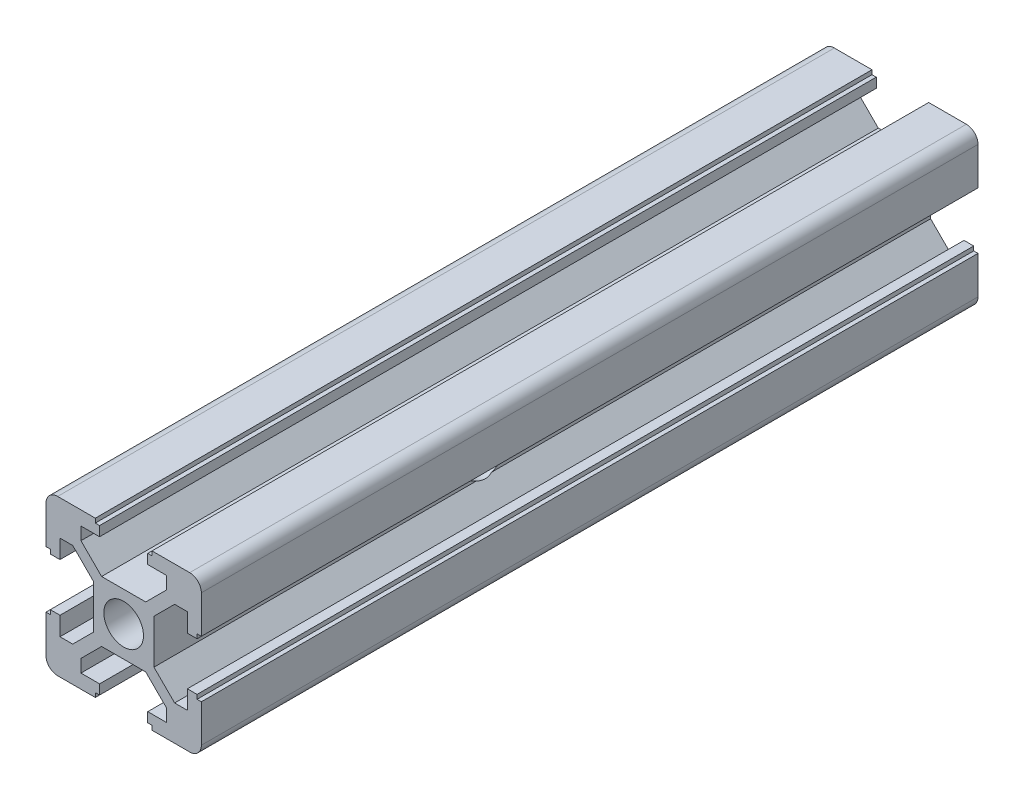
SolidWorks part; units mm, degrees
material "6063-T5"
ref_plane "前视基准面" through (0, 0, 0) normal (0, 0, 1) x (1, 0, 0)
ref_plane "上视基准面" through (0, 0, 0) normal (0, 1, 0) x (1, 0, 0)
ref_plane "右视基准面" through (0, 0, 0) normal (1, 0, 0) x (0, 0, -1)
sketch "草图2" plane through (0, 0, 0) normal (0, 0, 1) x (1, 0, 0)
  line L0 (-3.9, 2.8393) -> (-6.5607, 5.5)
  line L1 (-2.8393, 3.9) -> (2.8393, 3.9)
  line L2 (-3.9, 2.8393) -> (-3.9, -2.8393)
  line L3 (-2.8393, -3.9) -> (2.8393, -3.9)
  line L4 (3.9, 2.8393) -> (3.9, -2.8393)
  line L5 (-3.9, 3.9) -> (3.9, -3.9) construction
  line L6 (-3.9, -3.9) -> (3.9, 3.9) construction
  line L7 (-2.8393, 3.9) -> (-5.5, 6.5607)
  line L8 (-5.5, 6.5607) -> (-5.5, 8.2)
  line L9 (-5.5, 8.2) -> (-3.1, 8.2)
  line L10 (-3.1, 8.2) -> (-3.1, 9.45)
  line L11 (-3.1, 9.45) -> (-3.65, 9.45)
  line L12 (-3.65, 9.45) -> (-3.65, 10)
  line L13 (-3.65, 10) -> (-8.5, 10)
  line L14 (-6.5607, 5.5) -> (-8.2, 5.5)
  line L15 (-10, 3.65) -> (-10, 8.5)
  line L16 (-9.45, 3.65) -> (-10, 3.65)
  line L17 (-9.45, 3.1) -> (-9.45, 3.65)
  line L18 (-8.2, 3.1) -> (-9.45, 3.1)
  line L19 (-8.2, 5.5) -> (-8.2, 3.1)
  line L20 (2.8393, 3.9) -> (5.5, 6.5607)
  line L21 (3.9, 2.8393) -> (6.5607, 5.5)
  line L22 (6.5607, 5.5) -> (8.2, 5.5)
  line L23 (8.2, 5.5) -> (8.2, 3.1)
  line L24 (8.2, 3.1) -> (9.45, 3.1)
  line L25 (9.45, 3.1) -> (9.45, 3.65)
  line L26 (9.45, 3.65) -> (10, 3.65)
  line L27 (10, 3.65) -> (10, 8.5)
  line L28 (5.5, 6.5607) -> (5.5, 8.2)
  line L29 (3.65, 10) -> (8.5, 10)
  line L30 (3.65, 9.45) -> (3.65, 10)
  line L31 (3.1, 9.45) -> (3.65, 9.45)
  line L32 (3.1, 8.2) -> (3.1, 9.45)
  line L33 (5.5, 8.2) -> (3.1, 8.2)
  line L34 (3.9, -2.8393) -> (6.5607, -5.5)
  line L35 (2.8393, -3.9) -> (5.5, -6.5607)
  line L36 (5.5, -6.5607) -> (5.5, -8.2)
  line L37 (5.5, -8.2) -> (3.1, -8.2)
  line L38 (3.1, -8.2) -> (3.1, -9.45)
  line L39 (3.1, -9.45) -> (3.65, -9.45)
  line L40 (3.65, -9.45) -> (3.65, -10)
  line L41 (3.65, -10) -> (8.5, -10)
  line L42 (6.5607, -5.5) -> (8.2, -5.5)
  line L43 (10, -3.65) -> (10, -8.5)
  line L44 (9.45, -3.65) -> (10, -3.65)
  line L45 (9.45, -3.1) -> (9.45, -3.65)
  line L46 (8.2, -3.1) -> (9.45, -3.1)
  line L47 (8.2, -5.5) -> (8.2, -3.1)
  line L48 (-2.8393, -3.9) -> (-5.5, -6.5607)
  line L49 (-3.9, -2.8393) -> (-6.5607, -5.5)
  line L50 (-6.5607, -5.5) -> (-8.2, -5.5)
  line L51 (-8.2, -5.5) -> (-8.2, -3.1)
  line L52 (-8.2, -3.1) -> (-9.45, -3.1)
  line L53 (-9.45, -3.1) -> (-9.45, -3.65)
  line L54 (-9.45, -3.65) -> (-10, -3.65)
  line L55 (-10, -3.65) -> (-10, -8.5)
  line L56 (-5.5, -6.5607) -> (-5.5, -8.2)
  line L57 (-3.65, -10) -> (-8.5, -10)
  line L58 (-3.65, -9.45) -> (-3.65, -10)
  line L59 (-3.1, -9.45) -> (-3.65, -9.45)
  line L60 (-3.1, -8.2) -> (-3.1, -9.45)
  line L61 (-5.5, -8.2) -> (-3.1, -8.2)
  circle A0 centre (0, 0) radius 2.55
  arc A1 (-8.5, 10) -> (-10, 8.5) centre (-8.5, 8.5) ccw
  arc A2 (10, 8.5) -> (8.5, 10) centre (8.5, 8.5) ccw
  arc A3 (8.5, -10) -> (10, -8.5) centre (8.5, -8.5) ccw
  arc A4 (-10, -8.5) -> (-8.5, -10) centre (-8.5, -8.5) ccw
  point P25 (-10, 10)
  point P79 (0, 0)
  dimension "D1" = 5.1
  dimension "D9" = 1.5
  dimension "D2" = 7.8
  dimension "D3" = 1.5
  dimension "D4" = 10
  dimension "D5" = 3.1
  dimension "D6" = 0.55
  dimension "D7" = 1.8
  dimension "D8" = 5.5
  dimension "D11" = 3.9
  dimension "D10" = 4
extrude "凸台-拉伸1" add sketch "草图2" along normal blind 100
sketch "草图3" plane through (10, 0, 0) normal (1, 0, 0) x (0, 0, -1)
  circle A0 centre (-57.5, 0) radius 3
  circle A1 centre (-302.5, 0) radius 3
  dimension "D1" = 6
  dimension "D2" = 6
extrude "切除-拉伸1" cut sketch "草图3" against normal through all
